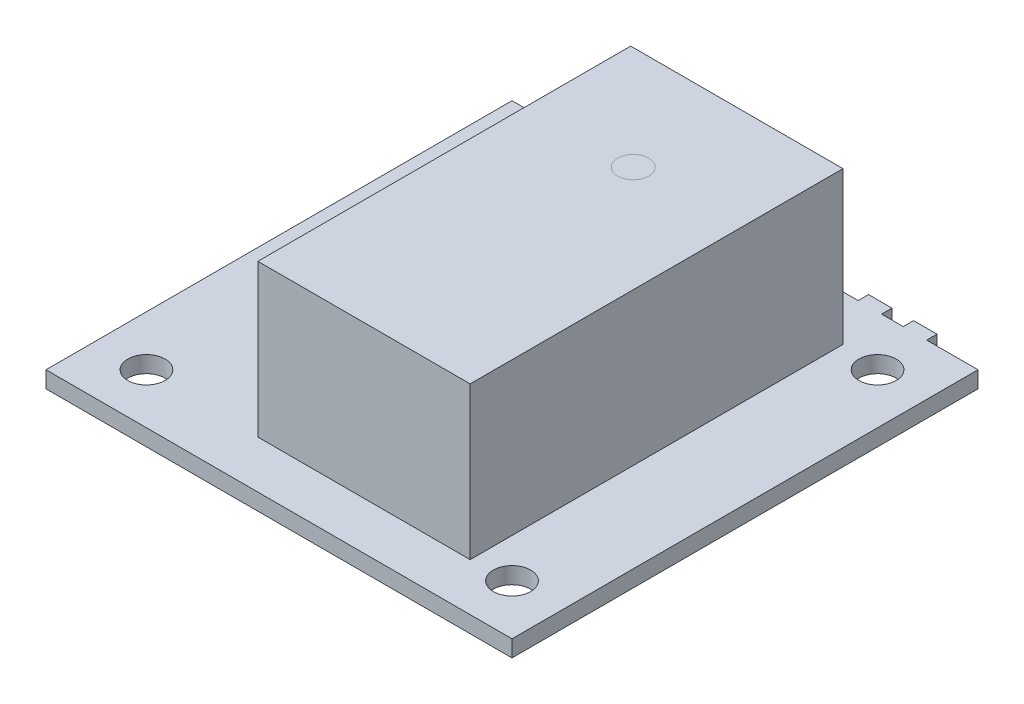
SolidWorks part; units mm, degrees
ref_plane "Front Plane" through (0, 0, 0) normal (0, 0, 1) x (1, 0, 0)
ref_plane "Top Plane" through (0, 0, 0) normal (0, 1, 0) x (1, 0, 0)
ref_plane "Right Plane" through (0, 0, 0) normal (1, 0, 0) x (0, 0, -1)
sketch "Sketch1" plane through (0, 0, 0) normal (0, 1, 0) x (1, 0, 0)
  line L1 (-22.5, -22.5) -> (22.5, -22.5)
  line L2 (-22.5, -22.5) -> (-22.5, 22.5)
  line L3 (-22.5, 22.5) -> (22.5, 22.5)
  line L4 (22.5, -22.5) -> (22.5, 22.5)
  line L5 (-22.5, -22.5) -> (22.5, 22.5) construction
  line L6 (-22.5, 22.5) -> (22.5, -22.5) construction
  line L8 (-17.65, 17.65) -> (17.65, 17.65) construction
  line L9 (-17.65, 17.65) -> (-17.65, -17.65) construction
  line L10 (-17.65, -17.65) -> (17.65, -17.65) construction
  line L11 (17.65, 17.65) -> (17.65, -17.65) construction
  line L12 (-17.65, 17.65) -> (17.65, -17.65) construction
  line L13 (-17.65, -17.65) -> (17.65, 17.65) construction
  circle A0 centre (-17.65, 17.65) radius 1.8
  circle A1 centre (17.65, 17.65) radius 1.8
  circle A2 centre (17.65, -17.65) radius 1.8
  circle A3 centre (-17.65, -17.65) radius 1.8
  point P0 (0, 0)
  point P6 (0, 0)
  point P15 (-15.85, 17.65)
  point P16 (15.85, 17.65)
  point P17 (17.65, 15.85)
  point P18 (17.65, -15.85)
  dimension "D3" = 3.6
  dimension "D4" = 31.7
  dimension "D5" = 31.7
  dimension "D1" = 45
  dimension "D2" = 45
extrude "Boss-Extrude1" add sketch "Sketch1" along normal mid plane 1.6
sketch "Sketch2" plane through (0, 0.8, 0) normal (0, 1, 0) x (1, 0, 0)
  line L0 (22.5, 22.5) -> (-22.5, 22.5) construction
  line L1 (-17.7022, 22.5) -> (-15.4374, 22.5)
  line L2 (-17.7022, 22.5) -> (-17.7022, 23.5)
  line L3 (-17.7022, 23.5) -> (-15.4374, 23.5)
  line L4 (-15.4374, 22.5) -> (-15.4374, 23.5)
  line L6 (-14.1634, 22.5) -> (-11.8985, 22.5)
  line L7 (-14.1634, 22.5) -> (-14.1634, 23.5)
  line L8 (-14.1634, 23.5) -> (-11.8985, 23.5)
  line L9 (-11.8985, 22.5) -> (-11.8985, 23.5)
  line L10 (-9.4213, 22.5) -> (-7.1565, 22.5)
  line L11 (-9.4213, 22.5) -> (-9.4213, 23.5)
  line L12 (-9.4213, 23.5) -> (-7.1565, 23.5)
  line L13 (-7.1565, 22.5) -> (-7.1565, 23.5)
  line L14 (-5.2455, 22.5) -> (-2.9807, 22.5)
  line L15 (-5.2455, 22.5) -> (-5.2455, 23.5)
  line L16 (-5.2455, 23.5) -> (-2.9807, 23.5)
  line L17 (-2.9807, 22.5) -> (-2.9807, 23.5)
  line L18 (6.0079, 22.5) -> (8.2728, 22.5)
  line L19 (6.0079, 22.5) -> (6.0079, 23.5)
  line L20 (6.0079, 23.5) -> (8.2728, 23.5)
  line L21 (8.2728, 22.5) -> (8.2728, 23.5)
  line L22 (10.9269, 22.5) -> (13.1918, 22.5)
  line L23 (10.9269, 22.5) -> (10.9269, 23.5)
  line L24 (10.9269, 23.5) -> (13.1918, 23.5)
  line L25 (13.1918, 22.5) -> (13.1918, 23.5)
  line L26 (15.2797, 22.5) -> (17.5445, 22.5)
  line L27 (15.2797, 22.5) -> (15.2797, 23.5)
  line L28 (15.2797, 23.5) -> (17.5445, 23.5)
  line L29 (17.5445, 22.5) -> (17.5445, 23.5)
  dimension "D1" = 1
extrude "Boss-Extrude2" add sketch "Sketch2" against normal up to surface (1.6 mm away) up to face at (17.65, -0.8, 19.45)
sketch "Sketch3" plane through (0, 0.8, 0) normal (0, 1, 0) x (1, 0, 0)
  line L0 (22.5, -22.5) -> (22.5, 22.5) construction
  line L1 (-6.64, 18.1) -> (13.86, 18.1)
  line L2 (-6.64, 18.1) -> (-6.64, -17.9)
  line L3 (-6.64, -17.9) -> (13.86, -17.9)
  line L4 (13.86, 18.1) -> (13.86, -17.9)
  line L5 (-6.64, 18.1) -> (13.86, -17.9) construction
  line L6 (-6.64, -17.9) -> (13.86, 18.1) construction
  line L7 (-22.5, -22.5) -> (22.5, -22.5) construction
  point P0 (0, 0)
  dimension "D1" = 20.5
  dimension "D2" = 36
  dimension "D3" = 8.64
  dimension "D4" = 4.6
extrude "Spark Core" add sketch "Sketch3" along normal offset from surface (14.7 mm away) 16.3
sketch "Sketch4" plane through (0, 15.5, 0) normal (0, 1, 0) x (1, 0, 0)
  line L0 (3.61, 8.1) -> (-6.64, 8.1) construction
  line L1 (-6.64, -17.9) -> (-6.64, 18.1) construction
  line L2 (3.61, 8.1) -> (13.86, 8.1) construction
  line L3 (13.86, 18.1) -> (13.86, -17.9) construction
  line L4 (3.61, 8.1) -> (3.61, 18.1) construction
  line L5 (-6.64, 18.1) -> (13.86, 18.1) construction
  circle A0 centre (3.61, 8.1) radius 1.5
  dimension "D2" = 3
  dimension "D1" = 10
split line "LED"
